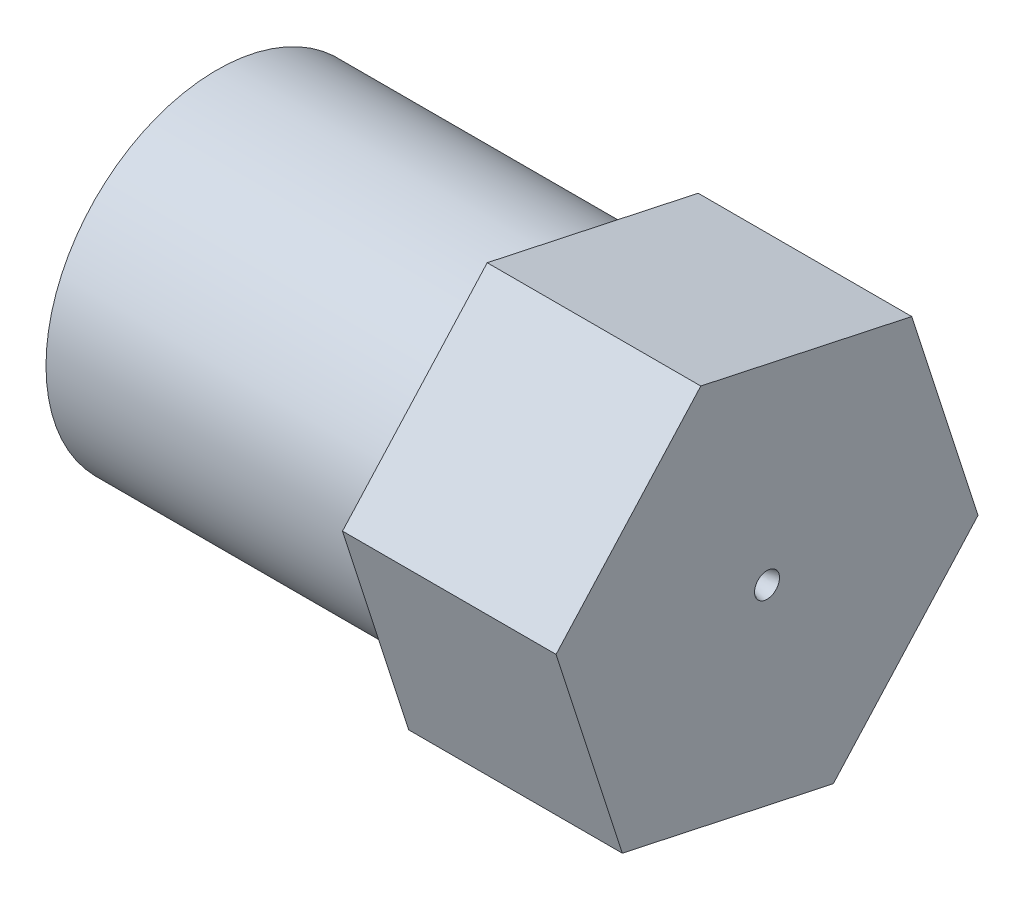
SolidWorks part; units mm, degrees
ref_plane "Front Plane" through (0, 0, 0) normal (0, 0, 1) x (1, 0, 0)
ref_plane "Top Plane" through (0, 0, 0) normal (0, 1, 0) x (1, 0, 0)
ref_plane "Right Plane" through (0, 0, 0) normal (1, 0, 0) x (0, 0, -1)
sketch "Sketch1" plane through (0, 0, 0) normal (0, 0, 1) x (1, 0, 0)
  line L0 (0, 0) -> (0.9695, 0) construction
  line L1 (0.0684, 0.5121) -> (0.9695, 0.84) construction
  line L2 (-0.5303, 0.7197) -> (-3.3257, 3.5151)
  line L3 (-31.75, 4.445) -> (-31.75, 10.16) construction
  line L4 (-5.5708, 4.445) -> (-31.75, 4.445) construction
  line L5 (-31.75, 10.16) -> (-11.73, 10.16)
  line L6 (0.9695, 10.16) -> (0.9695, 0.7416)
  line L7 (0.9695, 0.7416) -> (3.3384, 1.0745) construction
  line L8 (-11.73, 10.16) -> (0.9695, 10.16)
  line L9 (-5.5708, 4.445) -> (-13.462, 4.445)
  line L10 (-19.939, 5.461) -> (-19.939, 6.8199)
  line L11 (-20.066, 6.9469) -> (-24.892, 6.9469)
  line L12 (-24.892, 6.9469) -> (-24.892, 7.8994)
  line L13 (-25.019, 8.0264) -> (-31.115, 8.0264)
  line L14 (-31.75, 10.16) -> (-31.75, 8.6614)
  line L15 (0, 0) -> (-31.75, 0) construction
  line L16 (-13.462, 4.445) -> (-13.462, 4.699)
  line L17 (-13.589, 4.826) -> (-19.304, 4.826)
  arc A0 (-0.5303, 0.7197) -> (0, 0.5) centre (0, 1.25) ccw
  arc A1 (0, 0.5) -> (0.0684, 0.5121) centre (0, 0.7) ccw
  arc A2 (-3.3257, 3.5151) -> (-5.5708, 4.445) centre (-5.5708, 1.27) ccw
  arc A3 (-31.115, 8.0264) -> (-31.75, 8.6614) centre (-31.115, 8.6614) cw
  arc A4 (-19.304, 4.826) -> (-19.939, 5.461) centre (-19.304, 5.461) cw
  arc A5 (-13.462, 4.699) -> (-13.589, 4.826) centre (-13.589, 4.699) ccw
  arc A6 (-19.939, 6.8199) -> (-20.066, 6.9469) centre (-20.066, 6.8199) ccw
  arc A7 (-24.892, 7.8994) -> (-25.019, 8.0264) centre (-25.019, 7.8994) ccw
  parabola Q0 (0.9695, 0.7416) -> (0.0684, 0.5121) focus (0.7919, -1.3982) apex (0.0684, 0.5121)
  point P30 (-31.75, 8.0264)
  dimension "D3" = 0.75
  dimension "D4" = 0.2
  dimension "D11" = 3.175
  dimension "D12" = 8
  dimension "D14" = 6.9469
  dimension "D20" = 0.635
  dimension "D21" = 0.127
  dimension "D2" = 0.9695
  dimension "D5" = 0.7416
  dimension "D6" = 20
  dimension "D7" = 45
  dimension "D8" = 8.0264
  dimension "D9" = 31.75
  dimension "D10" = 10.16
  dimension "D15" = 4.445
  dimension "D16" = 6.858
  dimension "D17" = 11.811
  dimension "D18" = 18.288
  dimension "D19" = 4.826
  dimension "D22" = 0.5
revolve "Revolve1" add sketch "Sketch1" angle 360 about L0
sketch "Sketch4" plane through (0.9695, 0, 0) normal (1, 0, 0) x (0, 0, -1)
  line L1 (3.9404, -12.2116) -> (12.5458, -2.6933)
  line L2 (12.5458, -2.6933) -> (8.6054, 9.5183)
  line L3 (8.6054, 9.5183) -> (-3.9404, 12.2116)
  line L4 (-3.9404, 12.2116) -> (-12.5458, 2.6933)
  line L5 (-12.5458, 2.6933) -> (-8.6054, -9.5183)
  line L6 (-8.6054, -9.5183) -> (3.9404, -12.2116)
  circle A0 centre (0, 0) radius 10.16
  circle A1 centre (0, 0) radius 10.16 construction
  circle A2 centre (0, 0) radius 11.1125 construction
  circle M1 centre (0, 0) radius 10.16
  dimension "D1" = 22.225
extrude "Boss-Extrude1" add sketch "Sketch4" against normal blind 12.7 contours L4 L5 M1 | L3 L4 M1 | L2 L3 M1 | L1 L2 M1 | L6 L1 M1 | L5 L6 M1
fillet "Fillet1" radius 0.635 1 edges at (-11.7305, 0, -10.16)
equation "\"D3@Sketch1\" = 1.5 * \"D22@Sketch1\""
equation "\"D4@Sketch1\"  = .4 * \"D22@Sketch1\""
equation "\"D5@Sketch1\"=\"D22@Sketch1\" * ( \"er\") ^ .5"
equation "\"er\"= 2.2"
